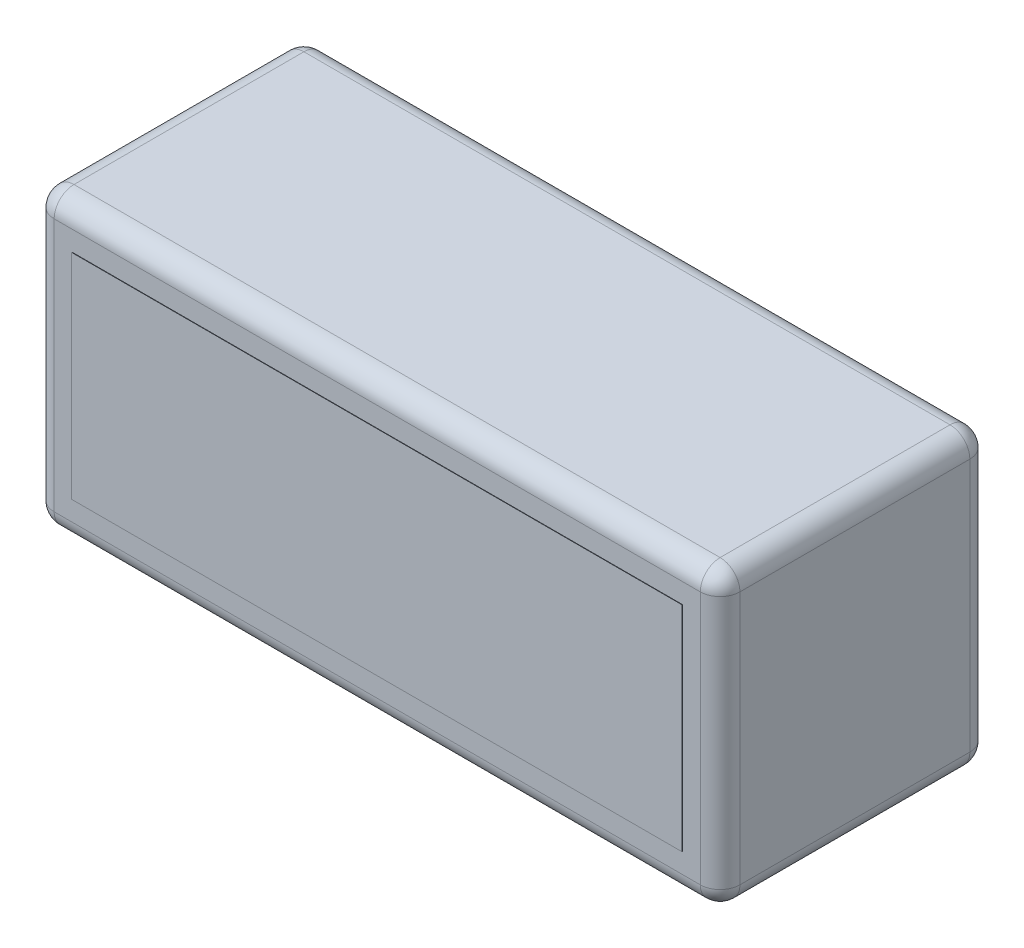
SolidWorks part; units mm, degrees
ref_plane "Front Plane" through (0, 0, 0) normal (0, 0, 1) x (1, 0, 0)
ref_plane "Top Plane" through (0, 0, 0) normal (0, 1, 0) x (1, 0, 0)
ref_plane "Right Plane" through (0, 0, 0) normal (1, 0, 0) x (0, 0, -1)
sketch "Sketch1" plane through (0, 0, 0) normal (0, 1, 0) x (1, 0, 0)
  line L1 (86.5, -34) -> (-86.5, -34)
  line L2 (86.5, -34) -> (86.5, 34)
  line L3 (86.5, 34) -> (-86.5, 34)
  line L4 (-86.5, -34) -> (-86.5, 34)
  line L5 (0, 34) -> (0, -34) construction
  line L6 (86.5, 0) -> (-86.5, 0) construction
  point P0 (0, 0)
  dimension "D1" = 173
  dimension "D2" = 68
extrude "Boss-Extrude1" add sketch "Sketch1" along normal blind 74
fillet "Fillet1" radius 5 12 edges at (86.5, 37, 34) (86.5, 74, 0) (86.5, 37, -34) (86.5, 0, 0) (0, 0, -34) (-86.5, 37, -34) (-86.5, 0, 0) (-86.5, 37, 34) (0, 0, 34) (0, 74, -34) (-86.5, 74, 0) (0, 74, 34)
sketch "Sketch2" plane through (0, 0, 34) normal (0, 0, 1) x (1, 0, 0)
  line L1 (76.9958, 10.0228) -> (-76.9958, 10.0228)
  line L2 (76.9958, 10.0228) -> (76.9958, 63.9772)
  line L3 (76.9958, 63.9772) -> (-76.9958, 63.9772)
  line L4 (-76.9958, 10.0228) -> (-76.9958, 63.9772)
  line L5 (0, 63.9772) -> (0, 10.0228) construction
  line L6 (76.9958, 37) -> (-76.9958, 37) construction
  point P0 (0, 37)
extrude "Boss-Extrude2" add sketch "Sketch2" along normal blind 0.1
sketch "Sketch3" plane through (0, 0, 34.1) normal (0, 0, 1) x (1, 0, 0)
  line L0 (77.6773, 239.0226) -> (908.3439, 239.0226) construction
sketch "Sketch4"
